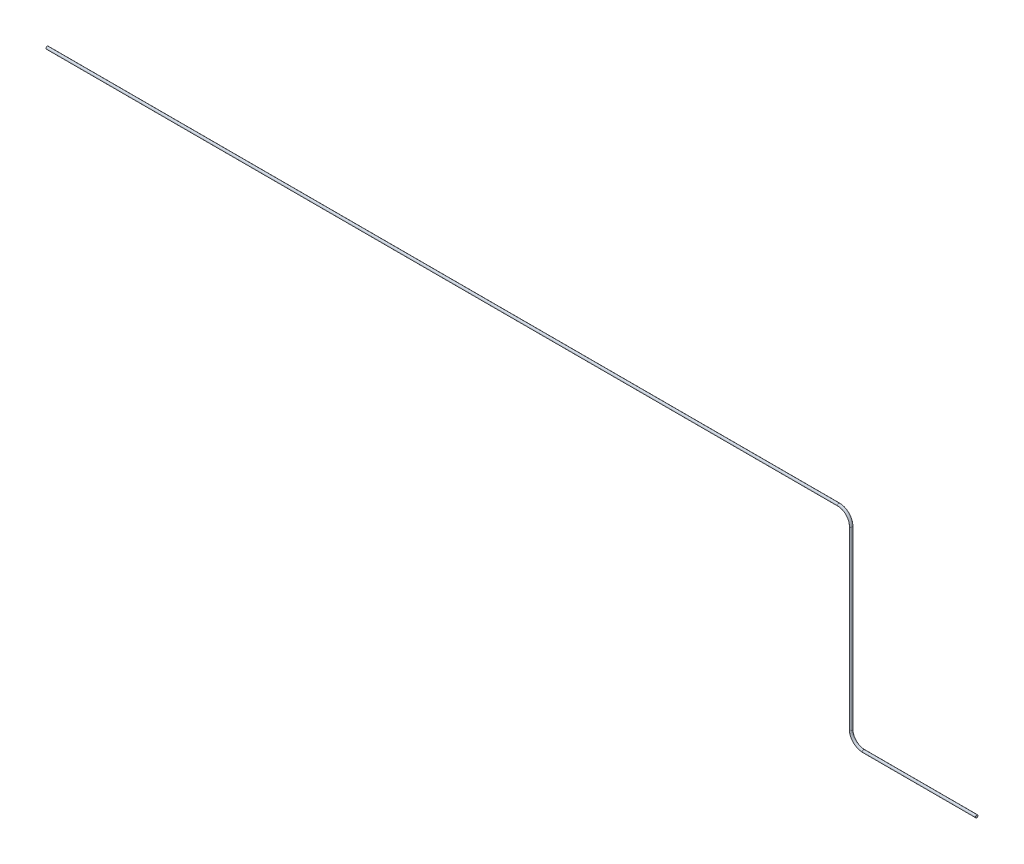
SolidWorks part; units mm, degrees
ref_plane "正面" through (0, 0, 0) normal (0, 0, 1) x (1, 0, 0)
ref_plane "平面" through (0, 0, 0) normal (0, 1, 0) x (1, 0, 0)
ref_plane "右側面" through (0, 0, 0) normal (1, 0, 0) x (0, 0, -1)
sketch "ｽｹｯﾁ1" plane through (0, 0, 0) normal (0, 0, 1) x (1, 0, 0)
  line L0 (-320, 40) -> (-5, 40)
  line L1 (0, 35) -> (0, -35)
  line L2 (5, -40) -> (50, -40)
  arc A0 (0, -35) -> (5, -40) centre (5, -35) ccw
  arc A1 (-5, 40) -> (0, 35) centre (-5, 35) cw
  point P7 (0, -40)
  point P10 (0, 40)
  dimension "D4" = 5
  dimension "D5" = 5
  dimension "D1" = 50
  dimension "D2" = 80
  dimension "D3" = 320
ref_plane "平面1" through (50, 0, 0) normal (1, 0, 0) x (0, 0, -1)
sketch "ｽｹｯﾁ2" plane through (50, 0, 0) normal (1, 0, 0) x (0, 0, -1)
  circle A0 centre (0, -40) radius 0.5
  dimension "D1" = 1
sweep "ｽｲｰﾌﾟ1" add profiles "ｽｹｯﾁ2" path "ｽｹｯﾁ1"
